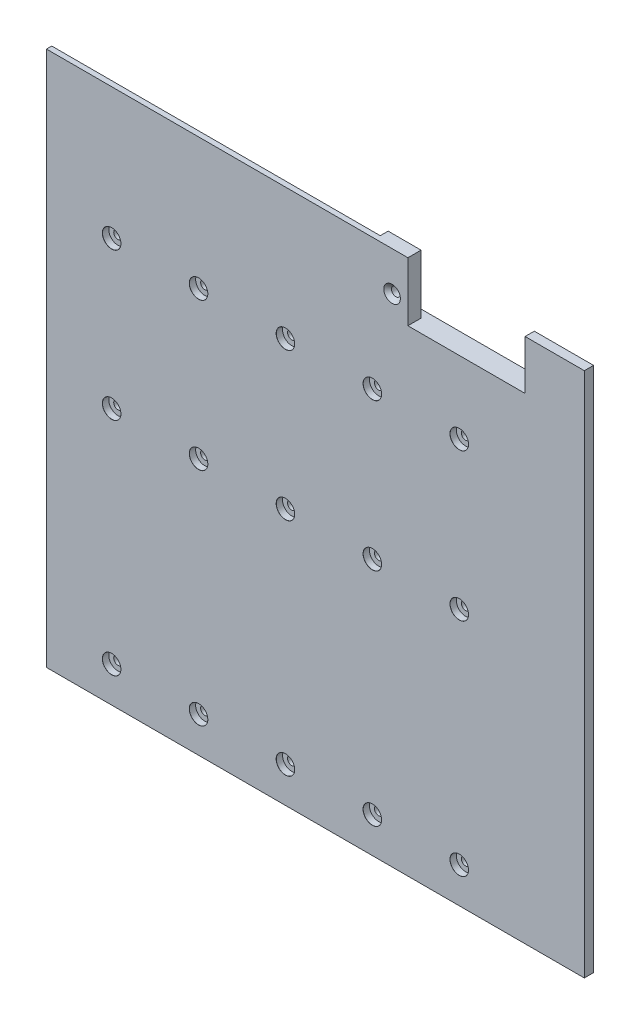
SolidWorks part; units mm, degrees
ref_plane "Plan de face" through (0, 0, 0) normal (0, 0, 1) x (1, 0, 0)
ref_plane "Plan de dessus" through (0, 0, 0) normal (0, 1, 0) x (1, 0, 0)
ref_plane "Plan de droite" through (0, 0, 0) normal (1, 0, 0) x (0, 0, -1)
sketch "Esquisse1" plane through (0, 0, 0) normal (0, 0, 1) x (1, 0, 0)
  line L1 (-204.25, -90.5) -> (204.25, -90.5)
  line L2 (-204.25, -90.5) -> (-204.25, 90.5)
  line L3 (-204.25, 90.5) -> (204.25, 90.5)
  line L4 (204.25, -90.5) -> (204.25, 90.5)
  line L5 (-204.25, -90.5) -> (204.25, 90.5) construction
  line L6 (-204.25, 90.5) -> (204.25, -90.5) construction
  point P0 (0, 0)
  dimension "D1" = 181
  dimension "D2" = 408.5
extrude "Boss.-Extru.1" add sketch "Esquisse1" along normal blind 8 contours L3 L4 L1 L2
hole_wizard "Chambrage pour vis à tête ronde bombée M31" positions "Esquisse2" profile "Esquisse3" counterbore size "M3" standard "Ansi Metric" end condition through all
sketch "Esquisse2" plane through (0, 0, 8) normal (0, 0, 1) x (1, 0, 0)
  point P0 (-173.25, 63)
  point P3 (-173.25, 7)
  point P6 (-173.25, -77)
sketch "Esquisse3" plane through (-173.25, 63, 8) normal (1, 0, 0) x (0, -1, 0)
  line L0 (0, 0) -> (0, 8)
  line L1 (0, 8) -> (1.6, 8)
  line L3 (1.6, 8) -> (1.6, 2.4)
  line L4 (3.5, 2.4) -> (1.6, 2.4)
  line L5 (3.5, 2.4) -> (3.5, 0.025)
  line L6 (3.5, 0.025) -> (3.525, 0)
  line L7 (3.525, 0) -> (0, 0)
  line L8 (-3.5, 0.025) -> (-3.525, 0) construction
  line L11 (0, -6.35) -> (0, 107.95) construction
  dimension "Diamètre du perçage jusqu'au prochain" = 3.2
  dimension "Profondeur du perçage jusqu'au prochain" = 8
  dimension "Diamètre du chambrage" = 7
  dimension "Profondeur du chambrage" = 2.4
  dimension "Diamètre du fraisage entrant" = 7.05
  dimension "Angle du fraisage entrant" = 90
pattern_linear "Répétition linéaire1" count 11 spacing 33 along (1, 0, 0) of "Chambrage pour vis à tête ronde bombée M31"
sketch "Esquisse6" plane through (0, 90.5, 0) normal (0, 1, 0) x (1, 0, 0)
  line L0 (-204.25, 0) -> (204.25, 0) construction
  line L1 (-204.25, 0) -> (-181.75, 0)
  line L2 (-204.25, 0) -> (-204.25, -4.5)
  line L3 (-204.25, -4.5) -> (-181.75, -4.5)
  line L4 (-181.75, 0) -> (-181.75, -4.5)
  line L6 (-204.25, -8) -> (204.25, -8) construction
  line L7 (0, -4.4) -> (0, 4.4) construction
  line L8 (181.75, 0) -> (181.75, -4.5)
  line L9 (204.25, -4.5) -> (181.75, -4.5)
  line L10 (204.25, 0) -> (204.25, -4.5)
  line L11 (204.25, 0) -> (181.75, 0)
  line L12 (-204.25, -8) -> (-204.25, 0) construction
  dimension "D2" = 3.5
  dimension "D3" = 22.5
extrude "Enlèv. mat.-Extru.1" cut sketch "Esquisse6" against normal up to next
sketch "Esquisse7" plane through (0, 0, 8) normal (0, 0, 1) x (1, 0, 0)
  line L1 (-204.25, 90.5) -> (-181.75, 90.5)
  line L2 (-204.25, 90.5) -> (-204.25, 109.225)
  line L3 (-204.25, 109.225) -> (-181.75, 109.225)
  line L4 (-181.75, 90.5) -> (-181.75, 109.225)
  dimension "D1" = 22.5
  dimension "D2" = 18.725
extrude "Boss.-Extru.2" add sketch "Esquisse7" against normal up to vertex
mirror "Symétrie1" about plane through (0, 0, 0) normal (1, 0, 0) of "Boss.-Extru.2"
sketch "Esquisse8" plane through (0, 0, 8) normal (0, 0, 1) x (1, 0, 0)
  line L0 (-181.75, 90.5) -> (181.75, 90.5) construction
  line L1 (-137.25, 90.5) -> (137.25, 90.5)
  line L2 (-137.25, 90.5) -> (-137.25, 112.875)
  line L3 (-137.25, 112.875) -> (137.25, 112.875)
  line L4 (137.25, 90.5) -> (137.25, 112.875)
  line L5 (-137.75, 91) -> (-137.75, 116.55) construction
  line L7 (124.75, 113.375) -> (137.75, 113.375) construction
  line L8 (137.75, 91) -> (137.75, 116.55) construction
  dimension "D1" = 0.5
  dimension "D2" = 0.5
  dimension "D3" = 0.5
extrude "Boss.-Extru.3" add sketch "Esquisse8" against normal blind 5
hole_wizard "Fraisage pour vis à tête fraisée M31" positions "Esquisse9" profile "Esquisse10" countersink size "M3" standard "Ansi Metric" end condition through all
sketch "Esquisse9" plane through (0, 0, 8) normal (0, 0, 1) x (1, 0, 0)
  point P0 (-131.25, 98)
  point P3 (131.25, 98)
sketch "Esquisse10" plane through (-131.25, 98, 8) normal (1, 0, 0) x (0, -1, 0)
  line L0 (0, 0) -> (0, 8)
  line L1 (0, 8) -> (1.7, 8)
  line L2 (1.7, 8) -> (1.7, 1.45)
  line L3 (1.7, 1.45) -> (3.15, 0)
  line L5 (3.15, 0) -> (0, 0)
  line L6 (-1.7, 1.45) -> (-3.15, 0) construction
  line L11 (0, -6.35) -> (0, 107.95) construction
  dimension "Diamètre du perçage jusqu'au prochain" = 3.4
  dimension "Profondeur du perçage jusqu'au prochain" = 8
  dimension "Diamètre du fraisage entrant" = 6.3
  dimension "Angle du fraisage entrant" = 90
ref_plane "Plan1" through (137.25, 112.875, 3) normal (-1, 0, 0) x (0, 0, 1)
sketch "Esquisse12" plane through (0, 0, 3) normal (0, 0, -1) x (-1, 0, 0)
  line L1 (-124.75, 91) -> (-124.75, 113.375) construction
  line L3 (124.75, 91) -> (124.75, 113.375) construction
  line L4 (137.25, 90.5) -> (137.25, 112.875)
  line L5 (137.25, 112.875) -> (-137.25, 112.875)
  line L6 (-137.25, 112.875) -> (-137.25, 90.5)
  line L7 (-137.25, 90.5) -> (137.25, 90.5)
  line L8 (124.75, 90.5) -> (124.75, 112.875)
  line L9 (124.75, 112.875) -> (-124.75, 112.875)
  line L10 (-124.75, 112.875) -> (-124.75, 90.5)
  line L11 (-124.75, 90.5) -> (124.75, 90.5)
  dimension "D1" = 0
extrude "Enlèv. mat.-Extru.2" cut sketch "Esquisse12" against normal blind 3
sketch "Esquisse13" plane through (0, 0, 0) normal (0, 0, -1) x (-1, 0, 0)
  line L0 (124.75, 112.875) -> (-124.75, 112.875) construction
  line L1 (204.25, -90.5) -> (0, -90.5)
  line L2 (204.25, -90.5) -> (204.25, 112.875)
  line L3 (204.25, 112.875) -> (0, 112.875)
  line L4 (0, -90.5) -> (0, 112.875)
extrude "Enlèv. mat.-Extru.3" cut sketch "Esquisse13" against normal blind 10
